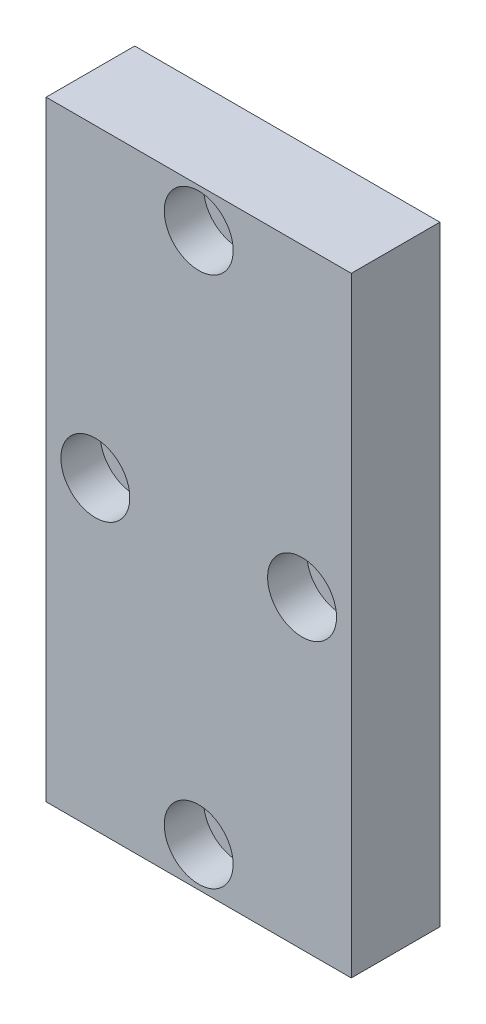
SolidWorks part; units mm, degrees
ref_plane "Front Plane" through (0, 0, 0) normal (0, 0, 1) x (1, 0, 0)
ref_plane "Top Plane" through (0, 0, 0) normal (0, 1, 0) x (1, 0, 0)
ref_plane "Right Plane" through (0, 0, 0) normal (1, 0, 0) x (0, 0, -1)
sketch "Sketch1" plane through (0, 0, 0) normal (0, 0, 1) x (1, 0, 0)
  line L1 (-15.5, 31) -> (15.5, 31)
  line L2 (-15.5, 31) -> (-15.5, -31)
  line L3 (-15.5, -31) -> (15.5, -31)
  line L4 (15.5, 31) -> (15.5, -31)
  line L5 (-15.5, 31) -> (15.5, -31) construction
  line L6 (-15.5, -31) -> (15.5, 31) construction
  point P4 (0, 0)
  dimension "D1" = 62
  dimension "D2" = 31
extrude "Boss-Extrude1" add sketch "Sketch1" along normal blind 9
sketch "Sketch2" plane through (0, 0, 9) normal (0, 0, 1) x (1, 0, 0)
  line L0 (0, 31) -> (0, -31) construction
  line L1 (15.5, 31) -> (-15.5, 31) construction
  line L2 (-15.5, -31) -> (15.5, -31) construction
  line L3 (-15.5, 0) -> (15.5, 0) construction
  line L4 (-15.5, 31) -> (-15.5, -31) construction
  line L5 (15.5, -31) -> (15.5, 31) construction
  circle A0 centre (0, 27) radius 2
  circle A1 centre (0, -27) radius 2
  circle A2 centre (10.5, 0) radius 2
  circle A3 centre (-10.5, 0) radius 2
  dimension "D1" = 4
  dimension "D2" = 4
  dimension "D3" = 4
  dimension "D4" = 5
extrude "Cut-Extrude1" cut sketch "Sketch2" against normal blind 10 contours A0 | A1 | A3 | A2
sketch "Sketch3" plane through (0, 0, 9) normal (0, 0, 1) x (1, 0, 0)
  line L0 (0, -31) -> (0, 31) construction
  line L1 (-15.5, -31) -> (15.5, -31) construction
  line L2 (15.5, 31) -> (-15.5, 31) construction
  line L3 (-15.5, 0) -> (15.5, 0) construction
  line L4 (-15.5, 31) -> (-15.5, -31) construction
  line L5 (15.5, -31) -> (15.5, 31) construction
  circle A0 centre (0, 27) radius 3.5
  circle A1 centre (10.5, 0) radius 3.5
  circle A2 centre (-10.5, 0) radius 3.5
  circle A3 centre (0, -27) radius 3.5
  dimension "D1" = 7
  dimension "D2" = 7
extrude "Cut-Extrude2" cut sketch "Sketch3" against normal blind 4
